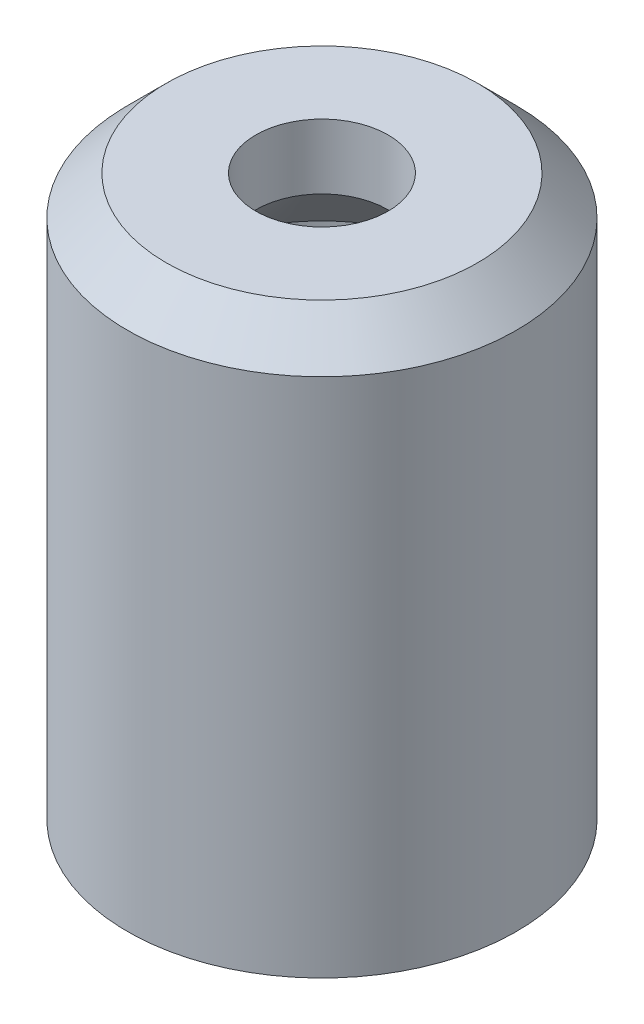
SolidWorks part; units mm, degrees
ref_plane "Front Plane" through (0, 0, 0) normal (0, 0, 1) x (1, 0, 0)
ref_plane "Top Plane" through (0, 0, 0) normal (0, 1, 0) x (1, 0, 0)
ref_plane "Right Plane" through (0, 0, 0) normal (1, 0, 0) x (0, 0, -1)
sketch "Sketch1" plane through (0, 0, 0) normal (0, 0, 1) x (1, 0, 0)
  line L0 (0, 0) -> (0, 13.7558) construction
  line L1 (-15, -2) -> (-15, 38.15)
  line L2 (-15, 38.15) -> (-12, 41.15)
  line L3 (-11.25, -2) -> (-11.25, 30)
  line L4 (-15, -2) -> (-11.25, -2)
  line L5 (0, 0) -> (-11, 0) construction
  line L6 (-11, 0) -> (-11, -2) construction
  line L7 (-11, -2) -> (-11.25, -2) construction
  line L8 (0, 30) -> (-10, 30) construction
  line L9 (-10, 30) -> (-10, 0) construction
  line L10 (-11.25, 30) -> (-5.1, 36.15)
  line L12 (-12, 41.15) -> (-5.1, 41.15)
  line L13 (-5.1, 41.15) -> (-5.1, 36.15)
  point P2 (-15, 41.7593)
  point P11 (-5.1, 42.0272)
  point P16 (-15, 36.7563)
  point P18 (-15, 42.3797)
  point P20 (-11, 30)
  point P21 (0, 0)
  dimension "D1" = 30
  dimension "D2" = 22.5
  dimension "D3" = 2
  dimension "D4" = 3.75
  dimension "D5" = 22
  dimension "D6" = 30
  dimension "D7" = 20
  dimension "D8" = 10.2
  dimension "D9" = 24
  dimension "D10" = 45
  dimension "D11" = 5
revolve "Revolve1" add sketch "Sketch1" angle 360 about L0
